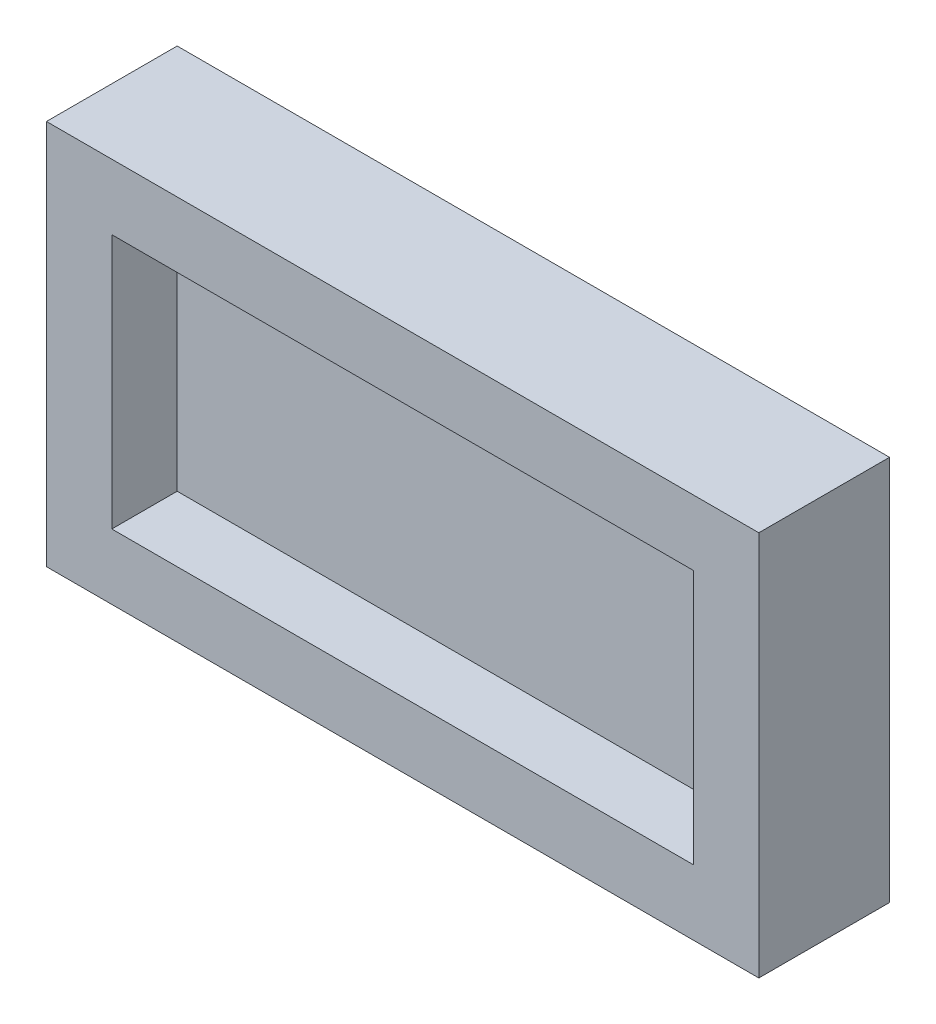
SolidWorks part; units mm, degrees
ref_plane "Front Plane" through (0, 0, 0) normal (0, 0, 1) x (1, 0, 0)
ref_plane "Top Plane" through (0, 0, 0) normal (0, 1, 0) x (1, 0, 0)
ref_plane "Right Plane" through (0, 0, 0) normal (1, 0, 0) x (0, 0, -1)
sketch "Sketch1" plane through (0, 0, 0) normal (0, 0, 1) x (1, 0, 0)
  line L0 (0, 0) -> (109, -59) construction
  line L1 (0, 0) -> (109, 0)
  line L2 (0, 0) -> (0, -59)
  line L3 (0, -59) -> (109, -59)
  line L4 (109, 0) -> (109, -59)
  line L5 (10, -10) -> (99, -10)
  line L6 (10, -10) -> (10, -49)
  line L7 (10, -49) -> (99, -49)
  line L8 (99, -10) -> (99, -49)
  line L9 (0, -59) -> (109, 0) construction
  line L10 (54.5, -59) -> (54.5, 0) construction
  line L11 (10, -10) -> (99, -49) construction
  line L12 (10, -49) -> (99, -10) construction
  dimension "D1" = 10
  dimension "D2" = 59
  dimension "D3" = 109
  dimension "D4" = 10
  dimension "D5" = 10
  dimension "10" = 10
extrude "Boss-Extrude1" add sketch "Sketch1" along normal blind 10
sketch "Sketch2" plane through (0, 0, 0) normal (0, 0, -1) x (-1, 0, 0)
  line L1 (-109, 0) -> (0, 0)
  line L2 (-109, 0) -> (-109, -59)
  line L3 (-109, -59) -> (0, -59)
  line L4 (0, 0) -> (0, -59)
extrude "Boss-Extrude2" add sketch "Sketch2" along normal blind 10
sketch "Sketch3" plane through (0, 0, -10) normal (0, 0, -1) x (-1, 0, 0)
  line L0 (-109, 0) -> (0, -59) construction
  line L1 (-109, -59) -> (0, 0) construction
  circle A0 centre (-54.5, -29.5) radius 10.0937
extrude "Boss-Extrude3" add sketch "Sketch3" along normal blind 10
